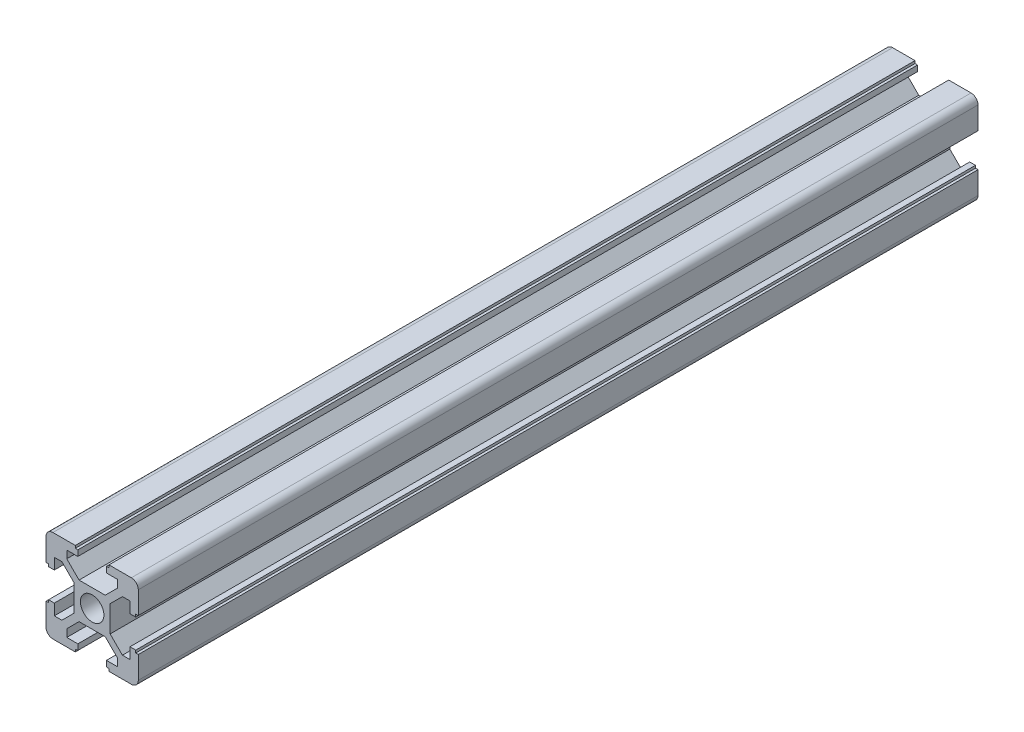
SolidWorks part; units mm, degrees
material "6063-T5"
ref_plane "前视基准面" through (0, 0, 0) normal (0, 0, 1) x (1, 0, 0)
ref_plane "上视基准面" through (0, 0, 0) normal (0, 1, 0) x (1, 0, 0)
ref_plane "右视基准面" through (0, 0, 0) normal (1, 0, 0) x (0, 0, -1)
sketch "草图1" plane through (0, 0, 0) normal (0, 0, 1) x (1, 0, 0)
  line L0 (-3.9, 2.8393) -> (-6.5607, 5.5)
  line L1 (-2.8393, 3.9) -> (2.8393, 3.9)
  line L2 (-3.9, 2.8393) -> (-3.9, -2.8393)
  line L3 (-2.8393, -3.9) -> (2.8393, -3.9)
  line L4 (3.9, 2.8393) -> (3.9, -2.8393)
  line L5 (-3.9, 3.9) -> (3.9, -3.9) construction
  line L6 (-3.9, -3.9) -> (3.9, 3.9) construction
  line L7 (-2.8393, 3.9) -> (-5.5, 6.5607)
  line L8 (-5.5, 6.5607) -> (-5.5, 8.2)
  line L9 (-5.5, 8.2) -> (-3.1, 8.2)
  line L10 (-3.1, 8.2) -> (-3.1, 9.45)
  line L11 (-3.1, 9.45) -> (-3.65, 9.45)
  line L12 (-3.65, 9.45) -> (-3.65, 10)
  line L13 (-3.65, 10) -> (-8.5, 10)
  line L14 (-6.5607, 5.5) -> (-8.2, 5.5)
  line L15 (-10, 3.65) -> (-10, 8.5)
  line L16 (-9.45, 3.65) -> (-10, 3.65)
  line L17 (-9.45, 3.1) -> (-9.45, 3.65)
  line L18 (-8.2, 3.1) -> (-9.45, 3.1)
  line L19 (-8.2, 5.5) -> (-8.2, 3.1)
  line L20 (2.8393, 3.9) -> (5.5, 6.5607)
  line L21 (3.9, 2.8393) -> (6.5607, 5.5)
  line L22 (6.5607, 5.5) -> (8.2, 5.5)
  line L23 (8.2, 5.5) -> (8.2, 3.1)
  line L24 (8.2, 3.1) -> (9.45, 3.1)
  line L25 (9.45, 3.1) -> (9.45, 3.65)
  line L26 (9.45, 3.65) -> (10, 3.65)
  line L27 (10, 3.65) -> (10, 8.5)
  line L28 (5.5, 6.5607) -> (5.5, 8.2)
  line L29 (3.65, 10) -> (8.5, 10)
  line L30 (3.65, 9.45) -> (3.65, 10)
  line L31 (3.1, 9.45) -> (3.65, 9.45)
  line L32 (3.1, 8.2) -> (3.1, 9.45)
  line L33 (5.5, 8.2) -> (3.1, 8.2)
  line L34 (3.9, -2.8393) -> (6.5607, -5.5)
  line L35 (2.8393, -3.9) -> (5.5, -6.5607)
  line L36 (5.5, -6.5607) -> (5.5, -8.2)
  line L37 (5.5, -8.2) -> (3.1, -8.2)
  line L38 (3.1, -8.2) -> (3.1, -9.45)
  line L39 (3.1, -9.45) -> (3.65, -9.45)
  line L40 (3.65, -9.45) -> (3.65, -10)
  line L41 (3.65, -10) -> (8.5, -10)
  line L42 (6.5607, -5.5) -> (8.2, -5.5)
  line L43 (10, -3.65) -> (10, -8.5)
  line L44 (9.45, -3.65) -> (10, -3.65)
  line L45 (9.45, -3.1) -> (9.45, -3.65)
  line L46 (8.2, -3.1) -> (9.45, -3.1)
  line L47 (8.2, -5.5) -> (8.2, -3.1)
  line L48 (-2.8393, -3.9) -> (-5.5, -6.5607)
  line L49 (-3.9, -2.8393) -> (-6.5607, -5.5)
  line L50 (-6.5607, -5.5) -> (-8.2, -5.5)
  line L51 (-8.2, -5.5) -> (-8.2, -3.1)
  line L52 (-8.2, -3.1) -> (-9.45, -3.1)
  line L53 (-9.45, -3.1) -> (-9.45, -3.65)
  line L54 (-9.45, -3.65) -> (-10, -3.65)
  line L55 (-10, -3.65) -> (-10, -8.5)
  line L56 (-5.5, -6.5607) -> (-5.5, -8.2)
  line L57 (-3.65, -10) -> (-8.5, -10)
  line L58 (-3.65, -9.45) -> (-3.65, -10)
  line L59 (-3.1, -9.45) -> (-3.65, -9.45)
  line L60 (-3.1, -8.2) -> (-3.1, -9.45)
  line L61 (-5.5, -8.2) -> (-3.1, -8.2)
  circle A0 centre (0, 0) radius 2.55
  arc A1 (-8.5, 10) -> (-10, 8.5) centre (-8.5, 8.5) ccw
  arc A2 (10, 8.5) -> (8.5, 10) centre (8.5, 8.5) ccw
  arc A3 (8.5, -10) -> (10, -8.5) centre (8.5, -8.5) ccw
  arc A4 (-10, -8.5) -> (-8.5, -10) centre (-8.5, -8.5) ccw
  point P74 (0, 0)
  dimension "D1" = 5.1
  dimension "D8" = 1.5
  dimension "D2" = 7.8
  dimension "D3" = 1.5
  dimension "D4" = 3.1
  dimension "D5" = 0.55
  dimension "D6" = 1.8
  dimension "D7" = 5.5
  dimension "D9" = 3.9
extrude "凸台-拉伸1" add sketch "草图1" along normal blind 182
